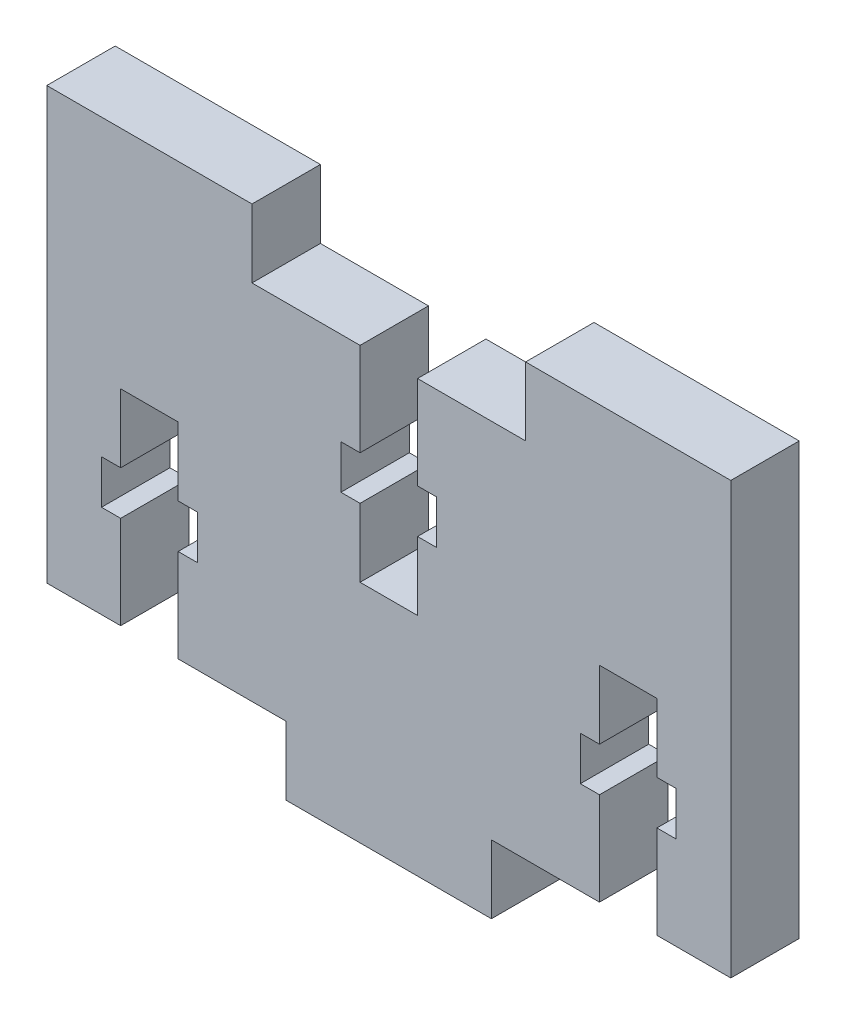
SolidWorks part; units mm, degrees
ref_plane "Front Plane" through (0, 0, 0) normal (0, 0, 1) x (1, 0, 0)
ref_plane "Top Plane" through (0, 0, 0) normal (0, 1, 0) x (1, 0, 0)
ref_plane "Right Plane" through (0, 0, 0) normal (1, 0, 0) x (0, 0, -1)
sketch "Sketch1" plane through (0, 0, 0) normal (0, 0, 1) x (1, 0, 0)
  line L0 (-25, 26.5) -> (-25, 7.7287) construction
  line L1 (0, 0) -> (-50, 0)
  line L2 (0, 0) -> (0, 26.5)
  line L3 (0, 26.5) -> (-50, 26.5)
  line L4 (-50, 0) -> (-50, 26.5)
  line L5 (-40.4, 0) -> (-44.6, 0)
  line L6 (-40.4, 0) -> (-40.4, 15)
  line L7 (-40.4, 15) -> (-44.6, 15)
  line L8 (-44.6, 0) -> (-44.6, 15)
  line L9 (-46, 10) -> (-39, 10)
  line L10 (-46, 10) -> (-46, 6.8)
  line L11 (-46, 6.8) -> (-39, 6.8)
  line L12 (-39, 10) -> (-39, 6.8)
  line L13 (-11, 10) -> (-11, 6.8)
  line L14 (-4, 6.8) -> (-11, 6.8)
  line L15 (-4, 10) -> (-4, 6.8)
  line L16 (-4, 10) -> (-11, 10)
  line L17 (-5.4, 0) -> (-5.4, 15)
  line L18 (-9.6, 15) -> (-5.4, 15)
  line L19 (-9.6, 0) -> (-9.6, 15)
  line L20 (-9.6, 0) -> (-5.4, 0)
  line L21 (0, 31.5) -> (-15, 31.5)
  line L22 (-22.9, 26.5) -> (-27.1, 26.5)
  line L23 (-22.9, 26.5) -> (-22.9, 11.5)
  line L24 (-22.9, 11.5) -> (-27.1, 11.5)
  line L25 (-27.1, 26.5) -> (-27.1, 11.5)
  line L26 (-28.5, 19.7) -> (-21.5, 19.7)
  line L27 (-28.5, 19.7) -> (-28.5, 16.5)
  line L28 (-28.5, 16.5) -> (-21.5, 16.5)
  line L29 (-21.5, 19.7) -> (-21.5, 16.5)
  line L30 (-50, 26.5) -> (-35, 26.5)
  line L31 (-50, 26.5) -> (-50, 31.5)
  line L32 (-50, 31.5) -> (-35, 31.5)
  line L33 (-35, 26.5) -> (-35, 31.5)
  line L34 (-15, 26.5) -> (-15, 31.5)
  line L35 (0, 26.5) -> (-15, 26.5)
  line L36 (0, 26.5) -> (0, 31.5)
  line L37 (0, 13.25) -> (7.0299, 13.25) construction
  line L47 (-32.5, 0) -> (-17.5, 0)
  line L48 (-32.5, 0) -> (-32.5, -5)
  line L49 (-32.5, -5) -> (-17.5, -5)
  line L50 (-17.5, 0) -> (-17.5, -5)
  point P13 (-42.5, 6.8)
  point P14 (-42.5, 15)
  point P33 (-25, 16.5)
  point P34 (-25, 11.5)
  point P47 (-25, -5)
  dimension "D1" = 26.5
  dimension "D2" = 50
  dimension "D3" = 7
  dimension "D4" = 4.2
  dimension "D5" = 6.8
  dimension "D6" = 3.2
  dimension "D7" = 7.5
  dimension "D8" = 15
  dimension "D9" = 15
  dimension "D10" = 6.8
  dimension "D11" = 3.2
  dimension "D12" = 7
  dimension "D13" = 4.2
  dimension "D14" = 5
  dimension "D15" = 15
  dimension "D16" = 5
  dimension "D17" = 15
extrude "Boss-Extrude1" add sketch "Sketch1" along normal blind 5
